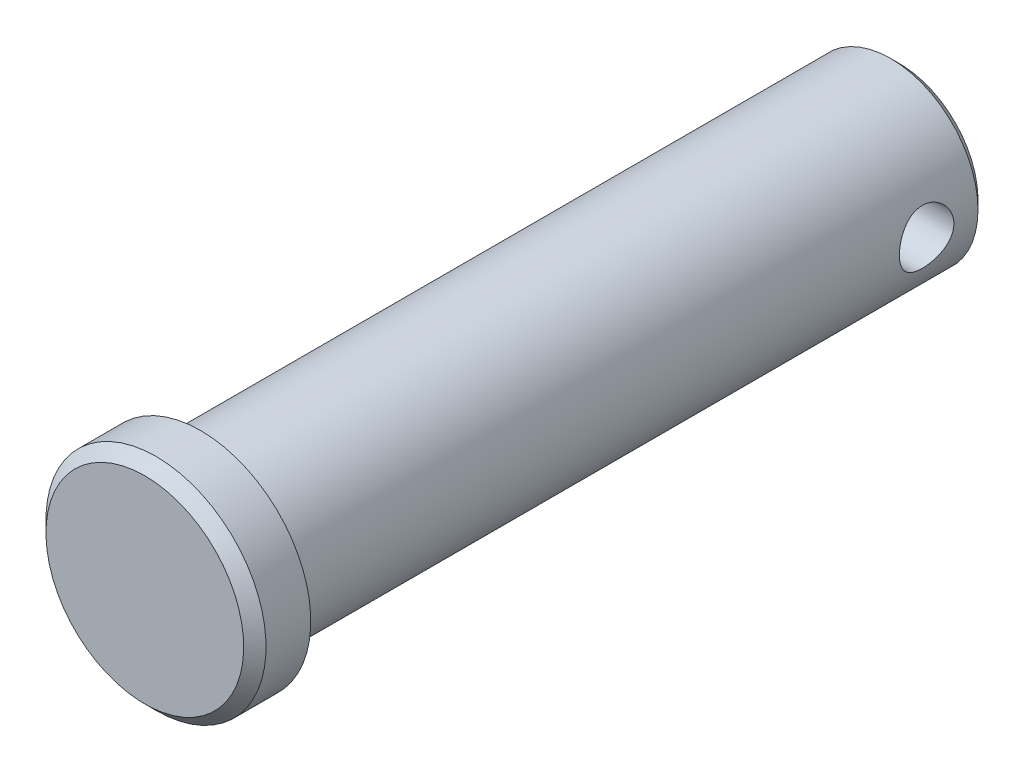
SolidWorks part; units mm, degrees
ref_plane "Front" through (0, 0, 0) normal (0, 0, 1) x (1, 0, 0)
ref_plane "Top" through (0, 0, 0) normal (0, 1, 0) x (1, 0, 0)
ref_plane "Right" through (0, 0, 0) normal (1, 0, 0) x (0, 0, -1)
sketch "Sketch1" plane through (0, 0, 0) normal (1, 0, 0) x (0, 0, -1)
  line L0 (0, 0) -> (50.8, 0) construction
  line L1 (0, 0) -> (-4.064, 0) construction
  line L2 (50.8, 6.35) -> (50.8, -6.35) construction
  line L3 (0, 8.001) -> (0, -8.001) construction
  line L4 (44.45, 0) -> (48.4124, 0) construction
  line L5 (50.8, 6.35) -> (0, 6.35) construction
  line L6 (50.8, -6.35) -> (0, -6.35) construction
  line L7 (44.45, 0) -> (44.45, -6.35) construction
  circle A1 centre (46.4312, 0) radius 1.5875
  point P10 (50.8, 0)
  point P12 (0, 0)
  point P13 (46.4312, 0)
  point P14 (-4.064, 8.001)
  point P17 (46.4312, 0)
  point P18 (44.45, 0)
  point P21 (-4.064, -8.001)
  dimension "For Maximum Cotter Pin Diameter" = 3.175
  dimension "Length" = 50.8
  dimension "Diameter" = 12.7
  dimension "Through Hole Diameter" = 3.9624
  dimension "Usable Length" = 44.45
  dimension "Head Height" = 4.064
  dimension "Head Diameter" = 16.002
sketch "Sketch4" plane through (0, 0, 0) normal (1, 0, 0) x (0, 0, -1)
  line L0 (-4.064, 0) -> (50.8, 0)
  line L1 (50.8, 0) -> (50.8, 6.35)
  line L2 (50.8, 6.35) -> (0, 6.35)
  line L3 (0, 8.001) -> (0, -8.001) construction
  line L4 (0, 6.35) -> (0, 8.001)
  line L5 (0, 8.001) -> (-4.064, 8.001)
  line L6 (-4.064, 8.001) -> (-4.064, 0)
revolve "Revolve1" add sketch "Sketch4" angle 360 about L0
sketch "Sketch2" plane through (0, 0, 6.35) normal (-1, 0, 0) x (0, 0, 1)
  circle A0 centre (-52.7812, 0) radius 1.9812
extrude "Cut-Extrude1" cut sketch "Sketch2" against normal through all and the other way through all
chamfer "Chamfer1" distance 0.8128 angle 45 1 edges at (0, -8.001, 4.064)
chamfer "Chamfer2" distance 0.635 angle 45 1 edges at (0, -6.35, -50.8)
equation "\"D1@Chamfer1\" = \"Head Height@Sketch1\" * .2"
equation "\"D1@Chamfer2\" = \"Diameter@Sketch1\" * .05"
